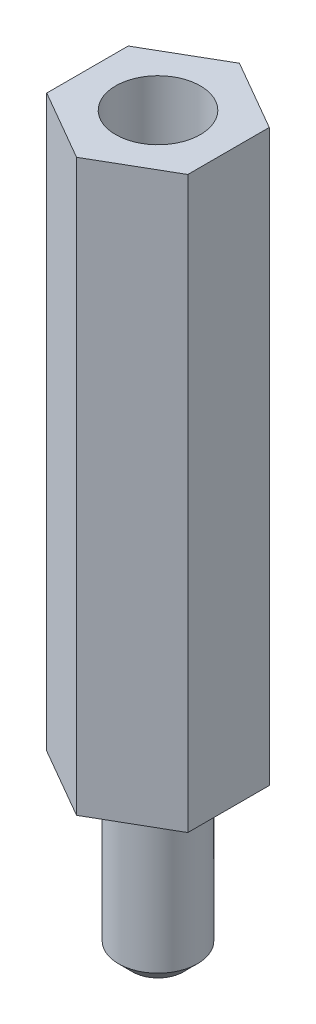
SolidWorks part; units mm, degrees
ref_plane "Спереди" through (0, 0, 0) normal (0, 0, 1) x (1, 0, 0)
ref_plane "Сверху" through (0, 0, 0) normal (0, 1, 0) x (1, 0, 0)
ref_plane "Справа" through (0, 0, 0) normal (1, 0, 0) x (0, 0, -1)
sketch "Эскиз1" plane through (0, 0, 0) normal (0, 1, 0) x (1, 0, 0)
  line L1 (0, 2.8868) -> (-2.5, 1.4434)
  line L2 (-2.5, 1.4434) -> (-2.5, -1.4434)
  line L3 (-2.5, -1.4434) -> (0, -2.8868)
  line L4 (0, -2.8868) -> (2.5, -1.4434)
  line L5 (2.5, -1.4434) -> (2.5, 1.4434)
  line L6 (2.5, 1.4434) -> (0, 2.8868)
  circle A0 centre (0, 0) radius 2.5 construction
  dimension "D1" = 5
extrude "Бобышка-Вытянуть1" add sketch "Эскиз1" along normal blind 20.2
sketch "Эскиз2" plane through (0, 0, 0) normal (0, -1, 0) x (1, 0, 0)
  circle A0 centre (0, 0) radius 1.4
  dimension "D1" = 2.8
extrude "Бобышка-Вытянуть2" add sketch "Эскиз2" along normal blind 5.8
chamfer "Фаска1" distance 0.5 angle 45 1 edges at (0, -5.8, -1.4)
sketch "Эскиз3" plane through (0, 20.2, 0) normal (0, 1, 0) x (1, 0, 0)
  circle A0 centre (0, 0) radius 1.5
  dimension "D1" = 3
extrude "Вырез-Вытянуть1" cut sketch "Эскиз3" against normal blind 7
